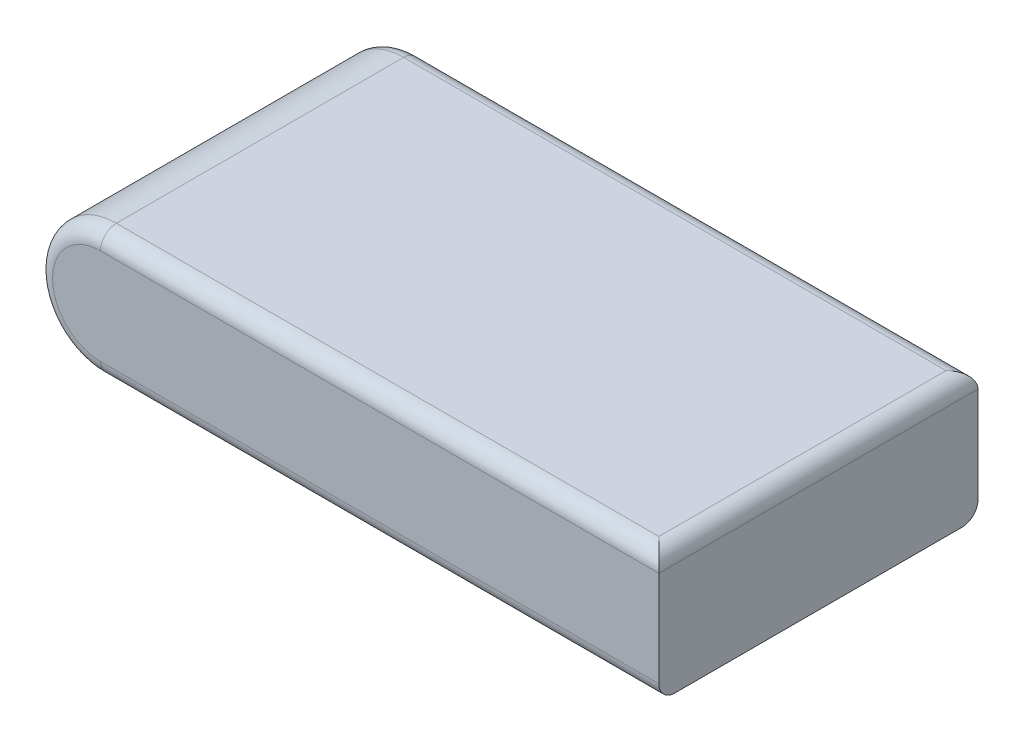
SolidWorks part; units mm, degrees
ref_plane "Спереди" through (0, 0, 0) normal (0, 0, 1) x (1, 0, 0)
ref_plane "Сверху" through (0, 0, 0) normal (0, 1, 0) x (1, 0, 0)
ref_plane "Справа" through (0, 0, 0) normal (1, 0, 0) x (0, 0, -1)
sketch "Эскиз1" plane through (0, 0, 0) normal (0, 0, 1) x (1, 0, 0)
  line L0 (-17.5, 4) -> (-17.5, -4) construction
  line L1 (17.5, -4) -> (-17.5, -4)
  line L2 (17.5, -4) -> (17.5, 4)
  line L3 (17.5, 4) -> (-17.5, 4)
  line L5 (17.5, -4) -> (-17.5, 4) construction
  line L6 (17.5, 4) -> (-17.5, -4) construction
  arc A0 (-17.5, -4) -> (-17.5, 4) centre (-17.5, 0) cw
  point P0 (0, 0)
  point P6 (-21.5, 0)
  point P8 (17.5, 0)
  dimension "D1" = 8
  dimension "D2" = 39
extrude "Бобышка-Вытянуть1" add sketch "Эскиз1" along normal blind 20
fillet "Скругление1" radius 1 7 edges at (0, -4, 20) (-21.5, 0, 20) (0, -4, 0) (-21.5, 0, 0) (17.5, 4, 10) (0, 4, 20) (0, 4, 0)
